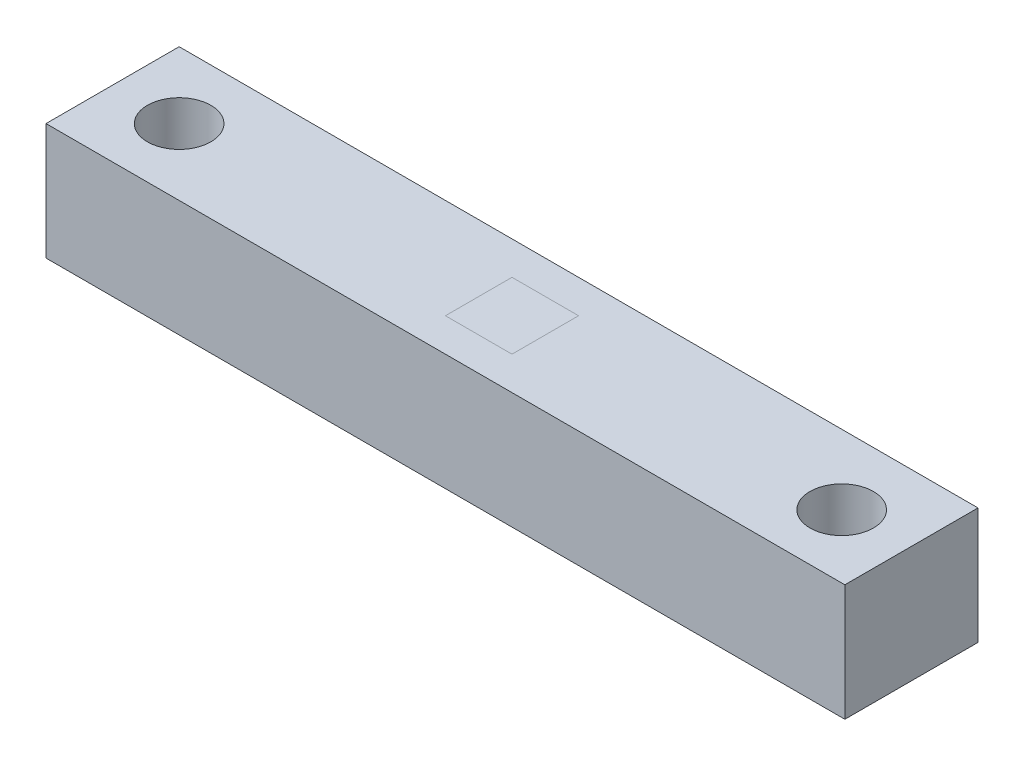
SolidWorks part; units mm, degrees
material "6061 Alloy"
ref_plane "Front Plane" through (0, 0, 0) normal (0, 0, 1) x (1, 0, 0)
ref_plane "Top Plane" through (0, 0, 0) normal (0, 1, 0) x (1, 0, 0)
ref_plane "Right Plane" through (0, 0, 0) normal (1, 0, 0) x (0, 0, -1)
sketch "Sketch1" plane through (0, 0, 0) normal (0, 0, 1) x (1, 0, 0)
  line L1 (120, -17.5) -> (-120, -17.5)
  line L2 (120, -17.5) -> (120, 17.5)
  line L3 (120, 17.5) -> (-120, 17.5)
  line L4 (-120, -17.5) -> (-120, 17.5)
  line L5 (120, -17.5) -> (-120, 17.5) construction
  line L6 (120, 17.5) -> (-120, -17.5) construction
  point P0 (0, 0)
  dimension "D1" = 240
  dimension "D2" = 35
extrude "Boss-Extrude1" add sketch "Sketch1" along normal blind 40
sketch "Sketch3" plane through (0, 17.5, 0) normal (0, 1, 0) x (1, 0, 0)
  line L0 (120, 0) -> (-120, 0) construction
  line L1 (-120, -40) -> (-120, 0) construction
  line L2 (120, -40) -> (-120, -40) construction
  circle A0 centre (-100, -20) radius 9.525
  circle A1 centre (100, -20.95) radius 9.525
  dimension "D4" = 19.05
  dimension "D1" = 20
  dimension "D2" = 200
  dimension "D3" = 20
  dimension "D5" = 19.05
extrude "Cut-Extrude4" cut sketch "Sketch3" against normal through all
sketch "Sketch4" plane through (0, 17.5, 0) normal (0, 1, 0) x (1, 0, 0)
  line L0 (-120, -40) -> (-120, 0) construction
  line L1 (10, -30) -> (-10, -30)
  line L2 (10, -30) -> (10, -10)
  line L3 (10, -10) -> (-10, -10)
  line L4 (-10, -30) -> (-10, -10)
  line L5 (10, -30) -> (-10, -10) construction
  line L6 (10, -10) -> (-10, -30) construction
  line L8 (120, -40) -> (-120, -40) construction
  point P0 (0, -20)
  dimension "D1" = 20
  dimension "D2" = 20
  dimension "D3" = 110
  dimension "D4" = 10
split line "Split Line1"
